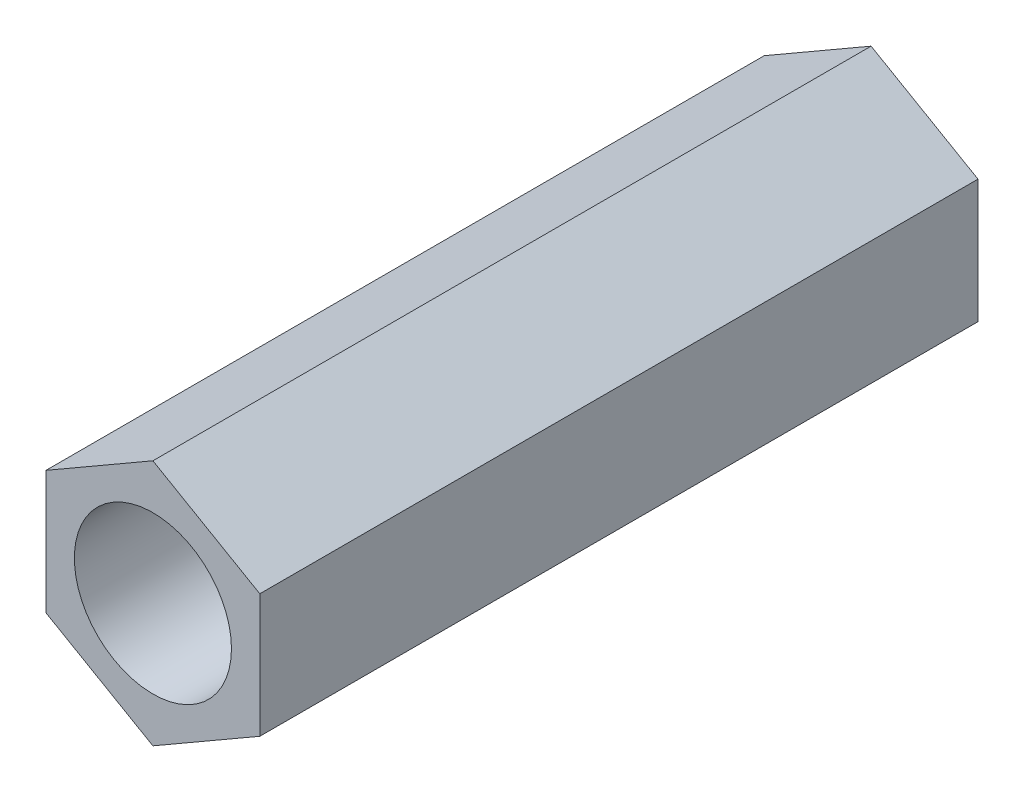
SolidWorks part; units mm, degrees
ref_plane "Front Plane" through (0, 0, 0) normal (0, 0, 1) x (1, 0, 0)
ref_plane "Top Plane" through (0, 0, 0) normal (0, 1, 0) x (1, 0, 0)
ref_plane "Right Plane" through (0, 0, 0) normal (1, 0, 0) x (0, 0, -1)
sketch "Sketch1" plane through (0, 0, 0) normal (0, 0, 1) x (1, 0, 0)
  line L1 (0, 2.75) -> (-2.3816, 1.375)
  line L2 (-2.3816, 1.375) -> (-2.3816, -1.375)
  line L3 (-2.3816, -1.375) -> (0, -2.75)
  line L4 (0, -2.75) -> (2.3816, -1.375)
  line L5 (2.3816, -1.375) -> (2.3816, 1.375)
  line L6 (2.3816, 1.375) -> (0, 2.75)
  circle A0 centre (0, 0) radius 2.75 construction
  circle A1 centre (0, 0) radius 2.3816 construction
  dimension "D1" = 5.5
extrude "Boss-Extrude1" add sketch "Sketch1" along normal blind 16
sketch "Sketch2" plane through (0, 0, 16) normal (0, 0, 1) x (1, 0, 0)
  circle A0 centre (0, 0) radius 1.75
extrude "Cut-Extrude1" cut sketch "Sketch2" against normal through all
